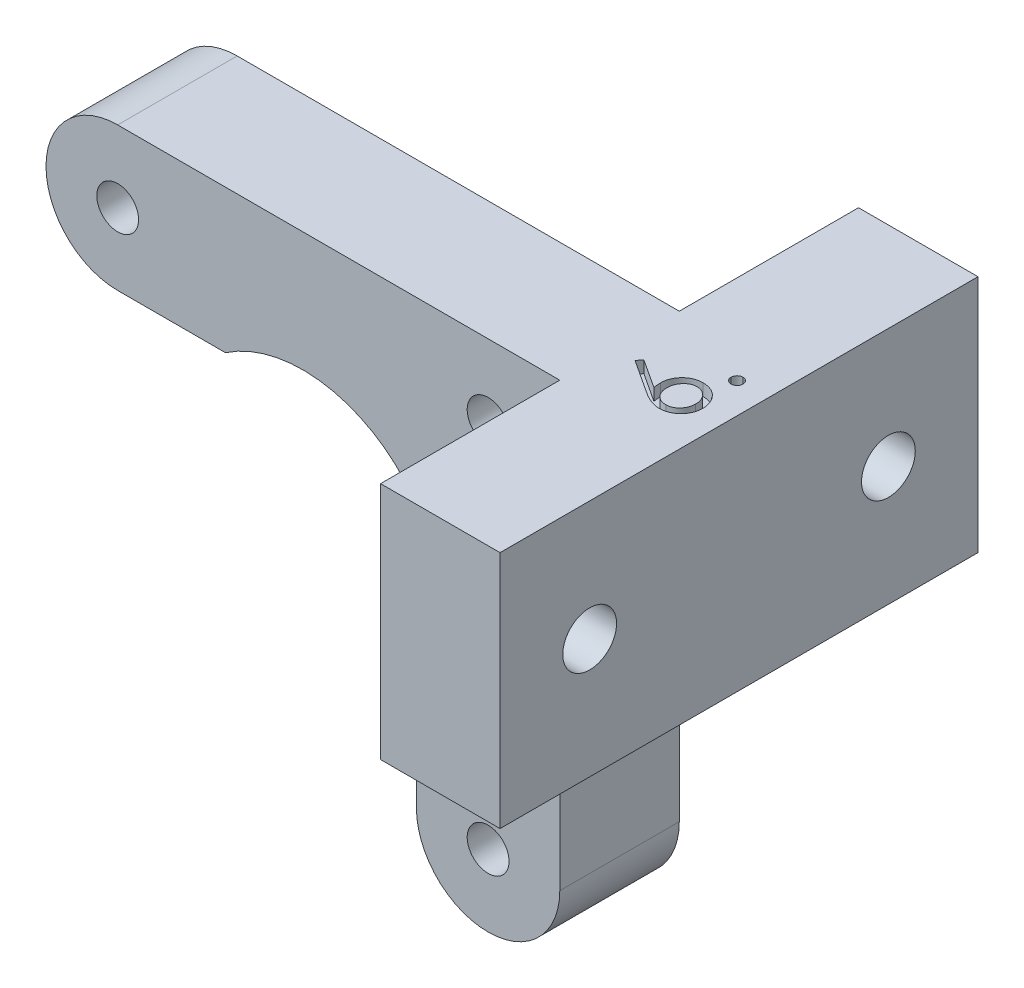
SolidWorks part; units mm, degrees
ref_plane "Alzado" through (0, 0, 0) normal (0, 0, 1) x (1, 0, 0)
ref_plane "Planta" through (0, 0, 0) normal (0, 1, 0) x (1, 0, 0)
ref_plane "Vista lateral" through (0, 0, 0) normal (1, 0, 0) x (0, 0, -1)
sketch "Croquis1" plane through (0, 0, 0) normal (0, 0, 1) x (1, 0, 0)
  line L0 (0, 6) -> (31, 6)
  line L1 (37, 0) -> (37, -31)
  line L2 (25, -31) -> (25, -21.9807)
  line L3 (37, 0) -> (37, 6)
  line L4 (0, -6) -> (9.0193, -6)
  line L5 (31, 6) -> (37, 6)
  circle A0 centre (0, 0) radius 1.75
  circle A1 centre (31, 0) radius 1.75
  circle A2 centre (31, -31) radius 1.75
  arc A3 (25, -21.9807) -> (9.0193, -6) centre (15.5, -15.5) ccw
  arc A4 (0, 6) -> (0, -6) centre (0, 0) ccw
  arc A6 (25, -31) -> (37, -31) centre (31, -31) ccw
  dimension "D1" = 3.5
  dimension "D2" = 3.5
  dimension "D3" = 31
  dimension "D4" = 3.5
  dimension "D6" = 31
  dimension "D7" = 15.5
  dimension "D8" = 15.5
  dimension "D9" = 23
extrude "Saliente-Extruir1" add sketch "Croquis1" along normal blind 10
sketch "Croquis3" plane through (37, 0, 0) normal (1, 0, 0) x (0, 0, -1)
  line L0 (-5, 6) -> (-5, 1) construction
  line L1 (-10, 6) -> (0, 6) construction
  line L2 (-5, 1) -> (-5, -4) construction
  line L4 (-25, -14) -> (15, -14)
  line L5 (-25, -14) -> (-25, 6)
  line L6 (-25, 6) -> (15, 6)
  line L7 (15, -14) -> (15, 6)
  line L8 (-25, -14) -> (15, 6) construction
  line L9 (-25, 6) -> (15, -14) construction
extrude "Saliente-Extruir2" add sketch "Croquis3" along normal blind 10
sketch "Croquis4" plane through (47, 0, 0) normal (1, 0, 0) x (0, 0, -1)
  line L0 (-25, 6) -> (-25, -4) construction
  line L1 (-25, 6) -> (-25, -14) construction
  line L2 (-25, -4) -> (-17.5, -4) construction
  line L3 (15, 6) -> (15, -4) construction
  line L4 (15, -14) -> (15, 6) construction
  line L5 (15, -4) -> (7.5, -4) construction
  circle A0 centre (-17.5, -4) radius 2.25
  circle A1 centre (7.5, -4) radius 2.25
extrude "Cortar-Extruir2" cut sketch "Croquis4" against normal blind 10
sketch "Croquis5" plane through (0, 6, 0) normal (0, 1, 0) x (1, 0, 0)
  line L0 (44.8733, -25) -> (44.8733, 15) construction
  line L1 (47, -25) -> (37, -25) construction
  line L2 (47, 15) -> (37, 15) construction
  text T0 "6." font "Century Gothic" height 6
extrude "Cortar-Extruir3" cut sketch "Croquis5" against normal blind 1
sketch "Croquis6" plane through (37, 0, 0) normal (-1, 0, 0) x (0, 0, 1)
  circle A0 centre (-7.5, -4) radius 3.6
extrude "Cortar-Extruir4" cut sketch "Croquis6" against normal blind 4.3
